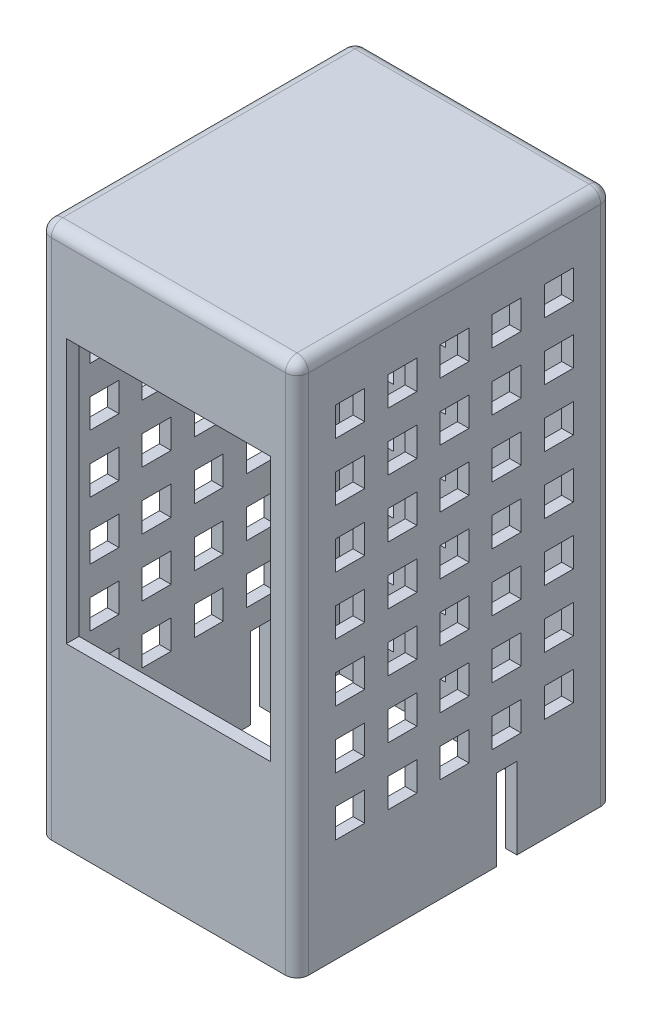
SolidWorks part; units mm, degrees
ref_plane "前视基准面" through (0, 0, 0) normal (0, 0, 1) x (1, 0, 0)
ref_plane "上视基准面" through (0, 0, 0) normal (0, 1, 0) x (1, 0, 0)
ref_plane "右视基准面" through (0, 0, 0) normal (1, 0, 0) x (0, 0, -1)
sketch "草图1" plane through (0, 0, 0) normal (0, 1, 0) x (1, 0, 0)
  line L1 (-20.2, -22.5) -> (20.2, -22.5)
  line L2 (-20.2, -22.5) -> (-20.2, 22.5)
  line L3 (-20.2, 22.5) -> (20.2, 22.5)
  line L4 (20.2, -22.5) -> (20.2, 22.5)
  line L5 (-20.2, -22.5) -> (20.2, 22.5) construction
  line L6 (-20.2, 22.5) -> (20.2, -22.5) construction
  line L7 (-22.2, -27.2) -> (22.2, -27.2)
  line L8 (-22.2, -27.2) -> (-22.2, 27.2)
  line L9 (-22.2, 27.2) -> (22.2, 27.2)
  line L10 (22.2, -27.2) -> (22.2, 27.2)
  line L11 (-22.2, -27.2) -> (22.2, 27.2) construction
  line L12 (-22.2, 27.2) -> (22.2, -27.2) construction
  point P0 (0, 0)
  point P6 (0, 0)
  dimension "D1" = 40.4
  dimension "D2" = 45
  dimension "D3" = 4.7
  dimension "D4" = 2
extrude "凸台-拉伸2" add sketch "草图1" along normal blind 92 contours L9 L10 L7 L8 | L3 L4 L1 L2
sketch "草图2" plane through (0, 0, 27.2) normal (0, 0, 1) x (1, 0, 0)
  line L1 (-17.6037, 30.6312) -> (17.6037, 30.6312)
  line L2 (-17.6037, 30.6312) -> (-17.6037, 76.2409)
  line L3 (-17.6037, 76.2409) -> (17.6037, 76.2409)
  line L4 (17.6037, 30.6312) -> (17.6037, 76.2409)
  line L5 (-17.6037, 30.6312) -> (17.6037, 76.2409) construction
  line L6 (-17.6037, 76.2409) -> (17.6037, 30.6312) construction
  point P0 (0, 53.436)
extrude "切除-拉伸1" cut sketch "草图2" against normal up to next
sketch "草图3" plane through (0, 0, 22.5) normal (0, 0, -1) x (-1, 0, 0)
  line L1 (-20.1, 25.7118) -> (20.1, 25.7118)
  line L2 (-20.1, 25.7118) -> (-20.1, 82.4118)
  line L3 (-20.1, 82.4118) -> (20.1, 82.4118)
  line L4 (20.1, 25.7118) -> (20.1, 82.4118)
  line L5 (-20.1, 25.7118) -> (20.1, 82.4118) construction
  line L6 (-20.1, 82.4118) -> (20.1, 25.7118) construction
  point P0 (0, 54.0618)
  dimension "D1" = 40.2
  dimension "D2" = 56.7
extrude "切除-拉伸2" cut sketch "草图3" against normal blind 2.5
sketch "草图10" plane through (-22.2, 0, 0) normal (-1, 0, 0) x (0, 0, 1)
  line L20 (6.5294, 17.873) -> (11.5294, 17.873)
  line L21 (6.5294, 17.873) -> (6.5294, 22.873)
  line L22 (6.5294, 22.873) -> (11.5294, 22.873)
  line L23 (11.5294, 17.873) -> (11.5294, 22.873)
  line L24 (-2.4706, 17.873) -> (2.5294, 17.873)
  line L25 (-2.4706, 17.873) -> (-2.4706, 22.873)
  line L26 (-2.4706, 22.873) -> (2.5294, 22.873)
  line L27 (2.5294, 17.873) -> (2.5294, 22.873)
  line L28 (-11.4706, 17.873) -> (-6.4706, 17.873)
  line L29 (-11.4706, 17.873) -> (-11.4706, 22.873)
  line L30 (-11.4706, 22.873) -> (-6.4706, 22.873)
  line L31 (-6.4706, 17.873) -> (-6.4706, 22.873)
  line L32 (-20.4706, 17.873) -> (-15.4706, 17.873)
  line L33 (-20.4706, 17.873) -> (-20.4706, 22.873)
  line L34 (-20.4706, 22.873) -> (-15.4706, 22.873)
  line L35 (-15.4706, 17.873) -> (-15.4706, 22.873)
  line L36 (6.5294, 27.873) -> (11.5294, 27.873)
  line L37 (6.5294, 27.873) -> (6.5294, 32.873)
  line L38 (6.5294, 32.873) -> (11.5294, 32.873)
  line L39 (11.5294, 27.873) -> (11.5294, 32.873)
  line L40 (-2.4706, 27.873) -> (2.5294, 27.873)
  line L41 (-2.4706, 27.873) -> (-2.4706, 32.873)
  line L42 (-2.4706, 32.873) -> (2.5294, 32.873)
  line L43 (2.5294, 27.873) -> (2.5294, 32.873)
  line L44 (-11.4706, 27.873) -> (-6.4706, 27.873)
  line L45 (-11.4706, 27.873) -> (-11.4706, 32.873)
  line L46 (-11.4706, 32.873) -> (-6.4706, 32.873)
  line L47 (-6.4706, 27.873) -> (-6.4706, 32.873)
  line L48 (-20.4706, 27.873) -> (-15.4706, 27.873)
  line L49 (-20.4706, 27.873) -> (-20.4706, 32.873)
  line L50 (-20.4706, 32.873) -> (-15.4706, 32.873)
  line L51 (-15.4706, 27.873) -> (-15.4706, 32.873)
  line L52 (6.5294, 37.873) -> (11.5294, 37.873)
  line L53 (6.5294, 37.873) -> (6.5294, 42.873)
  line L54 (6.5294, 42.873) -> (11.5294, 42.873)
  line L55 (11.5294, 37.873) -> (11.5294, 42.873)
  line L56 (-2.4706, 37.873) -> (2.5294, 37.873)
  line L57 (-2.4706, 37.873) -> (-2.4706, 42.873)
  line L58 (-2.4706, 42.873) -> (2.5294, 42.873)
  line L59 (2.5294, 37.873) -> (2.5294, 42.873)
  line L60 (-11.4706, 37.873) -> (-6.4706, 37.873)
  line L61 (-11.4706, 37.873) -> (-11.4706, 42.873)
  line L62 (-11.4706, 42.873) -> (-6.4706, 42.873)
  line L63 (-6.4706, 37.873) -> (-6.4706, 42.873)
  line L64 (-20.4706, 37.873) -> (-15.4706, 37.873)
  line L65 (-20.4706, 37.873) -> (-20.4706, 42.873)
  line L66 (-20.4706, 42.873) -> (-15.4706, 42.873)
  line L67 (-15.4706, 37.873) -> (-15.4706, 42.873)
  line L68 (6.5294, 47.873) -> (11.5294, 47.873)
  line L69 (6.5294, 47.873) -> (6.5294, 52.873)
  line L70 (6.5294, 52.873) -> (11.5294, 52.873)
  line L71 (11.5294, 47.873) -> (11.5294, 52.873)
  line L72 (-2.4706, 47.873) -> (2.5294, 47.873)
  line L73 (-2.4706, 47.873) -> (-2.4706, 52.873)
  line L74 (-2.4706, 52.873) -> (2.5294, 52.873)
  line L75 (2.5294, 47.873) -> (2.5294, 52.873)
  line L76 (-11.4706, 47.873) -> (-6.4706, 47.873)
  line L77 (-11.4706, 47.873) -> (-11.4706, 52.873)
  line L78 (-11.4706, 52.873) -> (-6.4706, 52.873)
  line L79 (-6.4706, 47.873) -> (-6.4706, 52.873)
  line L80 (-20.4706, 47.873) -> (-15.4706, 47.873)
  line L81 (-20.4706, 47.873) -> (-20.4706, 52.873)
  line L82 (-20.4706, 52.873) -> (-15.4706, 52.873)
  line L83 (-15.4706, 47.873) -> (-15.4706, 52.873)
  line L84 (6.5294, 57.873) -> (11.5294, 57.873)
  line L85 (6.5294, 57.873) -> (6.5294, 62.873)
  line L86 (6.5294, 62.873) -> (11.5294, 62.873)
  line L87 (11.5294, 57.873) -> (11.5294, 62.873)
  line L88 (-2.4706, 57.873) -> (2.5294, 57.873)
  line L89 (-2.4706, 57.873) -> (-2.4706, 62.873)
  line L90 (-2.4706, 62.873) -> (2.5294, 62.873)
  line L91 (2.5294, 57.873) -> (2.5294, 62.873)
  line L92 (-11.4706, 57.873) -> (-6.4706, 57.873)
  line L93 (-11.4706, 57.873) -> (-11.4706, 62.873)
  line L94 (-11.4706, 62.873) -> (-6.4706, 62.873)
  line L95 (-6.4706, 57.873) -> (-6.4706, 62.873)
  line L96 (-20.4706, 57.873) -> (-15.4706, 57.873)
  line L97 (-20.4706, 57.873) -> (-20.4706, 62.873)
  line L98 (-20.4706, 62.873) -> (-15.4706, 62.873)
  line L99 (-15.4706, 57.873) -> (-15.4706, 62.873)
  line L100 (6.5294, 67.873) -> (11.5294, 67.873)
  line L101 (6.5294, 67.873) -> (6.5294, 72.873)
  line L102 (6.5294, 72.873) -> (11.5294, 72.873)
  line L103 (11.5294, 67.873) -> (11.5294, 72.873)
  line L104 (-2.4706, 67.873) -> (2.5294, 67.873)
  line L105 (-2.4706, 67.873) -> (-2.4706, 72.873)
  line L106 (-2.4706, 72.873) -> (2.5294, 72.873)
  line L107 (2.5294, 67.873) -> (2.5294, 72.873)
  line L108 (-11.4706, 67.873) -> (-6.4706, 67.873)
  line L109 (-11.4706, 67.873) -> (-11.4706, 72.873)
  line L110 (-11.4706, 72.873) -> (-6.4706, 72.873)
  line L111 (-6.4706, 67.873) -> (-6.4706, 72.873)
  line L112 (-20.4706, 67.873) -> (-15.4706, 67.873)
  line L113 (-20.4706, 67.873) -> (-20.4706, 72.873)
  line L114 (-20.4706, 72.873) -> (-15.4706, 72.873)
  line L115 (-15.4706, 67.873) -> (-15.4706, 72.873)
  line L116 (6.5294, 77.873) -> (11.5294, 77.873)
  line L117 (6.5294, 77.873) -> (6.5294, 82.873)
  line L118 (6.5294, 82.873) -> (11.5294, 82.873)
  line L119 (11.5294, 77.873) -> (11.5294, 82.873)
  line L120 (-2.4706, 77.873) -> (2.5294, 77.873)
  line L121 (-2.4706, 77.873) -> (-2.4706, 82.873)
  line L122 (-2.4706, 82.873) -> (2.5294, 82.873)
  line L123 (2.5294, 77.873) -> (2.5294, 82.873)
  line L124 (-11.4706, 77.873) -> (-6.4706, 77.873)
  line L125 (-11.4706, 77.873) -> (-11.4706, 82.873)
  line L126 (-11.4706, 82.873) -> (-6.4706, 82.873)
  line L127 (-6.4706, 77.873) -> (-6.4706, 82.873)
  line L128 (-20.4706, 77.873) -> (-15.4706, 77.873)
  line L129 (-20.4706, 77.873) -> (-20.4706, 82.873)
  line L130 (-20.4706, 82.873) -> (-15.4706, 82.873)
  line L131 (-15.4706, 77.873) -> (-15.4706, 82.873)
  line L132 (15.5294, 17.873) -> (20.5294, 17.873)
  line L133 (15.5294, 17.873) -> (15.5294, 22.873)
  line L134 (15.5294, 22.873) -> (20.5294, 22.873)
  line L135 (20.5294, 17.873) -> (20.5294, 22.873)
  line L136 (15.5294, 27.873) -> (20.5294, 27.873)
  line L137 (15.5294, 27.873) -> (15.5294, 32.873)
  line L138 (15.5294, 32.873) -> (20.5294, 32.873)
  line L139 (20.5294, 27.873) -> (20.5294, 32.873)
  line L140 (15.5294, 37.873) -> (20.5294, 37.873)
  line L141 (15.5294, 37.873) -> (15.5294, 42.873)
  line L142 (15.5294, 42.873) -> (20.5294, 42.873)
  line L143 (20.5294, 37.873) -> (20.5294, 42.873)
  line L144 (15.5294, 47.873) -> (20.5294, 47.873)
  line L145 (15.5294, 47.873) -> (15.5294, 52.873)
  line L146 (15.5294, 52.873) -> (20.5294, 52.873)
  line L147 (20.5294, 47.873) -> (20.5294, 52.873)
  line L148 (15.5294, 57.873) -> (20.5294, 57.873)
  line L149 (15.5294, 57.873) -> (15.5294, 62.873)
  line L150 (15.5294, 62.873) -> (20.5294, 62.873)
  line L151 (20.5294, 57.873) -> (20.5294, 62.873)
  line L152 (15.5294, 67.873) -> (20.5294, 67.873)
  line L153 (15.5294, 67.873) -> (15.5294, 72.873)
  line L154 (15.5294, 72.873) -> (20.5294, 72.873)
  line L155 (20.5294, 67.873) -> (20.5294, 72.873)
  line L156 (15.5294, 77.873) -> (20.5294, 77.873)
  line L157 (15.5294, 77.873) -> (15.5294, 82.873)
  line L158 (15.5294, 82.873) -> (20.5294, 82.873)
  line L159 (20.5294, 77.873) -> (20.5294, 82.873)
extrude "切除-拉伸13" cut sketch "草图10" against normal through all
sketch "草图11" plane through (0, 0, -27.2) normal (0, 0, -1) x (-1, 0, 0)
  line L0 (10.8788, 7.8974) -> (15.8788, 7.8974)
  line L2 (22.2, 82.873) -> (22.2, 77.873) construction
  line L5 (10.8788, 7.8974) -> (10.8788, 12.8974)
  line L6 (10.8788, 12.8974) -> (15.8788, 12.8974)
  line L7 (15.8788, 7.8974) -> (15.8788, 12.8974)
  line L8 (1.8788, 7.8974) -> (6.8788, 7.8974)
  line L9 (1.8788, 7.8974) -> (1.8788, 12.8974)
  line L10 (1.8788, 12.8974) -> (6.8788, 12.8974)
  line L11 (6.8788, 7.8974) -> (6.8788, 12.8974)
  line L12 (-7.1212, 7.8974) -> (-2.1212, 7.8974)
  line L13 (-7.1212, 7.8974) -> (-7.1212, 12.8974)
  line L14 (-7.1212, 12.8974) -> (-2.1212, 12.8974)
  line L15 (-2.1212, 7.8974) -> (-2.1212, 12.8974)
  line L16 (-16.1212, 7.8974) -> (-11.1212, 7.8974)
  line L17 (-16.1212, 7.8974) -> (-16.1212, 12.8974)
  line L18 (-16.1212, 12.8974) -> (-11.1212, 12.8974)
  line L19 (-11.1212, 7.8974) -> (-11.1212, 12.8974)
  line L20 (10.8788, 17.8974) -> (15.8788, 17.8974)
  line L21 (10.8788, 17.8974) -> (10.8788, 22.8974)
  line L22 (10.8788, 22.8974) -> (15.8788, 22.8974)
  line L23 (15.8788, 17.8974) -> (15.8788, 22.8974)
  line L24 (1.8788, 17.8974) -> (6.8788, 17.8974)
  line L25 (1.8788, 17.8974) -> (1.8788, 22.8974)
  line L26 (1.8788, 22.8974) -> (6.8788, 22.8974)
  line L27 (6.8788, 17.8974) -> (6.8788, 22.8974)
  line L28 (-7.1212, 17.8974) -> (-2.1212, 17.8974)
  line L29 (-7.1212, 17.8974) -> (-7.1212, 22.8974)
  line L30 (-7.1212, 22.8974) -> (-2.1212, 22.8974)
  line L31 (-2.1212, 17.8974) -> (-2.1212, 22.8974)
  line L32 (-16.1212, 17.8974) -> (-11.1212, 17.8974)
  line L33 (-16.1212, 17.8974) -> (-16.1212, 22.8974)
  line L34 (-16.1212, 22.8974) -> (-11.1212, 22.8974)
  line L35 (-11.1212, 17.8974) -> (-11.1212, 22.8974)
  line L36 (10.8788, 27.8974) -> (15.8788, 27.8974)
  line L37 (10.8788, 27.8974) -> (10.8788, 32.8974)
  line L38 (10.8788, 32.8974) -> (15.8788, 32.8974)
  line L39 (15.8788, 27.8974) -> (15.8788, 32.8974)
  line L40 (1.8788, 27.8974) -> (6.8788, 27.8974)
  line L41 (1.8788, 27.8974) -> (1.8788, 32.8974)
  line L42 (1.8788, 32.8974) -> (6.8788, 32.8974)
  line L43 (6.8788, 27.8974) -> (6.8788, 32.8974)
  line L44 (-7.1212, 27.8974) -> (-2.1212, 27.8974)
  line L45 (-7.1212, 27.8974) -> (-7.1212, 32.8974)
  line L46 (-7.1212, 32.8974) -> (-2.1212, 32.8974)
  line L47 (-2.1212, 27.8974) -> (-2.1212, 32.8974)
  line L48 (-16.1212, 27.8974) -> (-11.1212, 27.8974)
  line L49 (-16.1212, 27.8974) -> (-16.1212, 32.8974)
  line L50 (-16.1212, 32.8974) -> (-11.1212, 32.8974)
  line L51 (-11.1212, 27.8974) -> (-11.1212, 32.8974)
  line L52 (10.8788, 37.8974) -> (15.8788, 37.8974)
  line L53 (10.8788, 37.8974) -> (10.8788, 42.8974)
  line L54 (10.8788, 42.8974) -> (15.8788, 42.8974)
  line L55 (15.8788, 37.8974) -> (15.8788, 42.8974)
  line L56 (1.8788, 37.8974) -> (6.8788, 37.8974)
  line L57 (1.8788, 37.8974) -> (1.8788, 42.8974)
  line L58 (1.8788, 42.8974) -> (6.8788, 42.8974)
  line L59 (6.8788, 37.8974) -> (6.8788, 42.8974)
  line L60 (-7.1212, 37.8974) -> (-2.1212, 37.8974)
  line L61 (-7.1212, 37.8974) -> (-7.1212, 42.8974)
  line L62 (-7.1212, 42.8974) -> (-2.1212, 42.8974)
  line L63 (-2.1212, 37.8974) -> (-2.1212, 42.8974)
  line L64 (-16.1212, 37.8974) -> (-11.1212, 37.8974)
  line L65 (-16.1212, 37.8974) -> (-16.1212, 42.8974)
  line L66 (-16.1212, 42.8974) -> (-11.1212, 42.8974)
  line L67 (-11.1212, 37.8974) -> (-11.1212, 42.8974)
  line L68 (10.8788, 47.8974) -> (15.8788, 47.8974)
  line L69 (10.8788, 47.8974) -> (10.8788, 52.8974)
  line L70 (10.8788, 52.8974) -> (15.8788, 52.8974)
  line L71 (15.8788, 47.8974) -> (15.8788, 52.8974)
  line L72 (1.8788, 47.8974) -> (6.8788, 47.8974)
  line L73 (1.8788, 47.8974) -> (1.8788, 52.8974)
  line L74 (1.8788, 52.8974) -> (6.8788, 52.8974)
  line L75 (6.8788, 47.8974) -> (6.8788, 52.8974)
  line L76 (-7.1212, 47.8974) -> (-2.1212, 47.8974)
  line L77 (-7.1212, 47.8974) -> (-7.1212, 52.8974)
  line L78 (-7.1212, 52.8974) -> (-2.1212, 52.8974)
  line L79 (-2.1212, 47.8974) -> (-2.1212, 52.8974)
  line L80 (-16.1212, 47.8974) -> (-11.1212, 47.8974)
  line L81 (-16.1212, 47.8974) -> (-16.1212, 52.8974)
  line L82 (-16.1212, 52.8974) -> (-11.1212, 52.8974)
  line L83 (-11.1212, 47.8974) -> (-11.1212, 52.8974)
  line L84 (10.8788, 57.8974) -> (15.8788, 57.8974)
  line L85 (10.8788, 57.8974) -> (10.8788, 62.8974)
  line L86 (10.8788, 62.8974) -> (15.8788, 62.8974)
  line L87 (15.8788, 57.8974) -> (15.8788, 62.8974)
  line L88 (1.8788, 57.8974) -> (6.8788, 57.8974)
  line L89 (1.8788, 57.8974) -> (1.8788, 62.8974)
  line L90 (1.8788, 62.8974) -> (6.8788, 62.8974)
  line L91 (6.8788, 57.8974) -> (6.8788, 62.8974)
  line L92 (-7.1212, 57.8974) -> (-2.1212, 57.8974)
  line L93 (-7.1212, 57.8974) -> (-7.1212, 62.8974)
  line L94 (-7.1212, 62.8974) -> (-2.1212, 62.8974)
  line L95 (-2.1212, 57.8974) -> (-2.1212, 62.8974)
  line L96 (-16.1212, 57.8974) -> (-11.1212, 57.8974)
  line L97 (-16.1212, 57.8974) -> (-16.1212, 62.8974)
  line L98 (-16.1212, 62.8974) -> (-11.1212, 62.8974)
  line L99 (-11.1212, 57.8974) -> (-11.1212, 62.8974)
  line L100 (10.8788, 67.8974) -> (15.8788, 67.8974)
  line L101 (10.8788, 67.8974) -> (10.8788, 72.8974)
  line L102 (10.8788, 72.8974) -> (15.8788, 72.8974)
  line L103 (15.8788, 67.8974) -> (15.8788, 72.8974)
  line L104 (1.8788, 67.8974) -> (6.8788, 67.8974)
  line L105 (1.8788, 67.8974) -> (1.8788, 72.8974)
  line L106 (1.8788, 72.8974) -> (6.8788, 72.8974)
  line L107 (6.8788, 67.8974) -> (6.8788, 72.8974)
  line L108 (-7.1212, 67.8974) -> (-2.1212, 67.8974)
  line L109 (-7.1212, 67.8974) -> (-7.1212, 72.8974)
  line L110 (-7.1212, 72.8974) -> (-2.1212, 72.8974)
  line L111 (-2.1212, 67.8974) -> (-2.1212, 72.8974)
  line L112 (-16.1212, 67.8974) -> (-11.1212, 67.8974)
  line L113 (-16.1212, 67.8974) -> (-16.1212, 72.8974)
  line L114 (-16.1212, 72.8974) -> (-11.1212, 72.8974)
  line L115 (-11.1212, 67.8974) -> (-11.1212, 72.8974)
  line L116 (10.8788, 77.8974) -> (15.8788, 77.8974)
  line L117 (10.8788, 77.8974) -> (10.8788, 82.8974)
  line L118 (10.8788, 82.8974) -> (15.8788, 82.8974)
  line L119 (15.8788, 77.8974) -> (15.8788, 82.8974)
  line L120 (1.8788, 77.8974) -> (6.8788, 77.8974)
  line L121 (1.8788, 77.8974) -> (1.8788, 82.8974)
  line L122 (1.8788, 82.8974) -> (6.8788, 82.8974)
  line L123 (6.8788, 77.8974) -> (6.8788, 82.8974)
  line L124 (-7.1212, 77.8974) -> (-2.1212, 77.8974)
  line L125 (-7.1212, 77.8974) -> (-7.1212, 82.8974)
  line L126 (-7.1212, 82.8974) -> (-2.1212, 82.8974)
  line L127 (-2.1212, 77.8974) -> (-2.1212, 82.8974)
  line L128 (-16.1212, 77.8974) -> (-11.1212, 77.8974)
  line L129 (-16.1212, 77.8974) -> (-16.1212, 82.8974)
  line L130 (-16.1212, 82.8974) -> (-11.1212, 82.8974)
  line L131 (-11.1212, 77.8974) -> (-11.1212, 82.8974)
  point P2 (22.2, 80.373)
extrude "切除-拉伸14" cut sketch "草图11" against normal up to next (4.7 mm away)
sketch "草图12" plane through (0, 92, 0) normal (0, 1, 0) x (1, 0, 0)
  line L1 (-22.2, 27.2) -> (22.2, 27.2)
  line L2 (-22.2, 27.2) -> (-22.2, -27.2)
  line L3 (-22.2, -27.2) -> (22.2, -27.2)
  line L4 (22.2, 27.2) -> (22.2, -27.2)
extrude "凸台-拉伸3" add sketch "草图12" against normal blind 2.5
sketch "草图13" plane through (0, 0, 0) normal (0, -1, 0) x (1, 0, 0)
  line L0 (-22.2, 27.2) -> (-22.2, -27.2) construction
  line L1 (-22.2, -10.7388) -> (22.2, -10.7388)
  line L2 (-22.2, -10.7388) -> (-22.2, -7.2162)
  line L3 (-22.2, -7.2162) -> (22.2, -7.2162)
  line L4 (22.2, -10.7388) -> (22.2, -7.2162)
  line L5 (22.2, 27.2) -> (22.2, -27.2) construction
extrude "切除-拉伸15" cut sketch "草图13" against normal blind 14
fillet "圆角1" radius 2 8 edges at (-22.2, 46, -27.2) (0, 92, -27.2) (22.2, 46, -27.2) (-22.2, 92, 0) (22.2, 92, 0) (-22.2, 46, 27.2) (22.2, 46, 27.2) (0, 92, 27.2)
